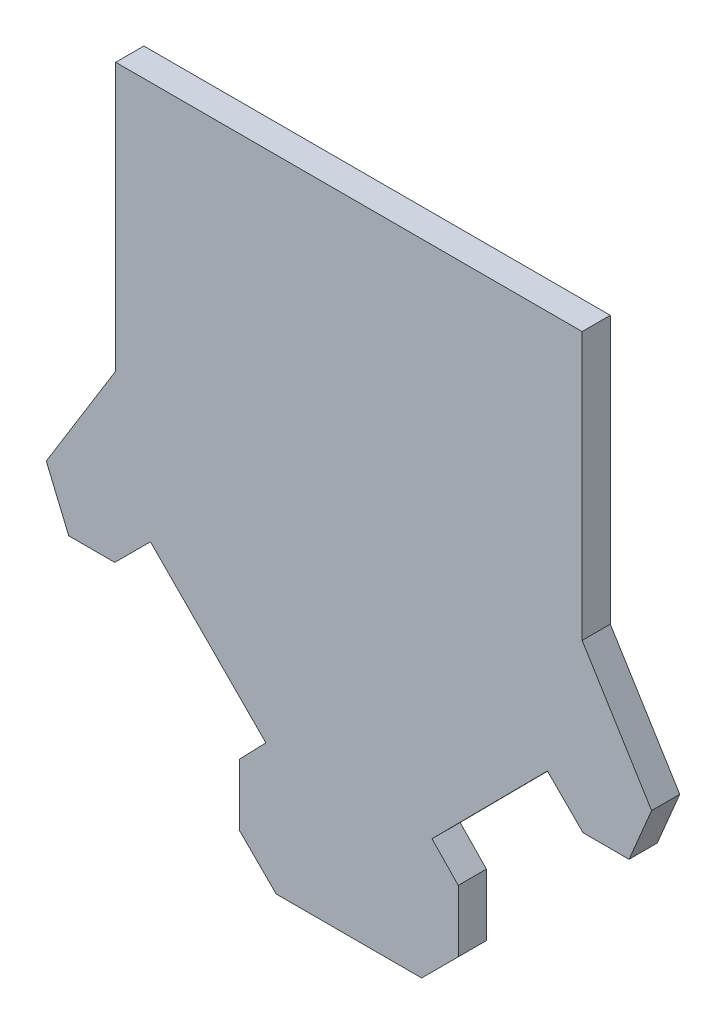
SolidWorks part; units mm, degrees
ref_plane "Front" through (0, 0, 0) normal (0, 0, 1) x (1, 0, 0)
ref_plane "Top" through (0, 0, 0) normal (0, 1, 0) x (1, 0, 0)
ref_plane "Right" through (0, 0, 0) normal (1, 0, 0) x (0, 0, -1)
sketch "Sketch1" plane through (0, 0, 0) normal (0, 0, 1) x (1, 0, 0)
  line L0 (0, 0) -> (0, -28.5)
  line L1 (0, -28.5) -> (-7.4, -40.5)
  line L2 (-7.4, -40.5) -> (-5, -46.2)
  line L3 (-5, -46.2) -> (-0.1, -46.2)
  line L4 (-0.1, -46.2) -> (3.7, -42.4)
  line L5 (3.7, -42.4) -> (16, -54.8)
  line L6 (16, -54.8) -> (13.2, -57.7)
  line L7 (13.2, -57.7) -> (13.2, -64.3)
  line L8 (13.2, -64.3) -> (17.1, -68.2)
  line L9 (17.1, -68.2) -> (32.6, -68.2)
  line L10 (24.85, -68.2) -> (24.85, 0)
  line L11 (49.7, 0) -> (0, 0)
  line L12 (36.5, -64.3) -> (32.6, -68.2)
  line L13 (36.5, -57.7) -> (36.5, -64.3)
  line L14 (33.7, -54.8) -> (36.5, -57.7)
  line L15 (46, -42.4) -> (33.7, -54.8)
  line L16 (49.8, -46.2) -> (46, -42.4)
  line L17 (54.7, -46.2) -> (49.8, -46.2)
  line L18 (57.1, -40.5) -> (54.7, -46.2)
  line L19 (49.7, -28.5) -> (57.1, -40.5)
  line L20 (49.7, 0) -> (49.7, -28.5)
  dimension "D1" = 28.5
  dimension "D2" = 7.4
  dimension "D3" = 12
  dimension "D4" = 2.4
  dimension "D5" = 5.7
  dimension "D6" = 4.9
  dimension "D7" = 3.8
  dimension "D8" = 3.8
  dimension "D9" = 12.3
  dimension "D10" = 12.4
  dimension "D11" = 2.8
  dimension "D12" = 2.9
  dimension "D13" = 6.6
  dimension "D14" = 3.9
  dimension "D15" = 3.9
  dimension "D16" = 7.75
extrude "Extrude1" add sketch "Sketch1" along normal blind 3 contours L20 L11 L10 L9 L12 L13 L14 L15 L16 L17 L18 L19 | L10 L11 L0 L1 L2 L3 L4 L5 L6 L7 L8 L9
